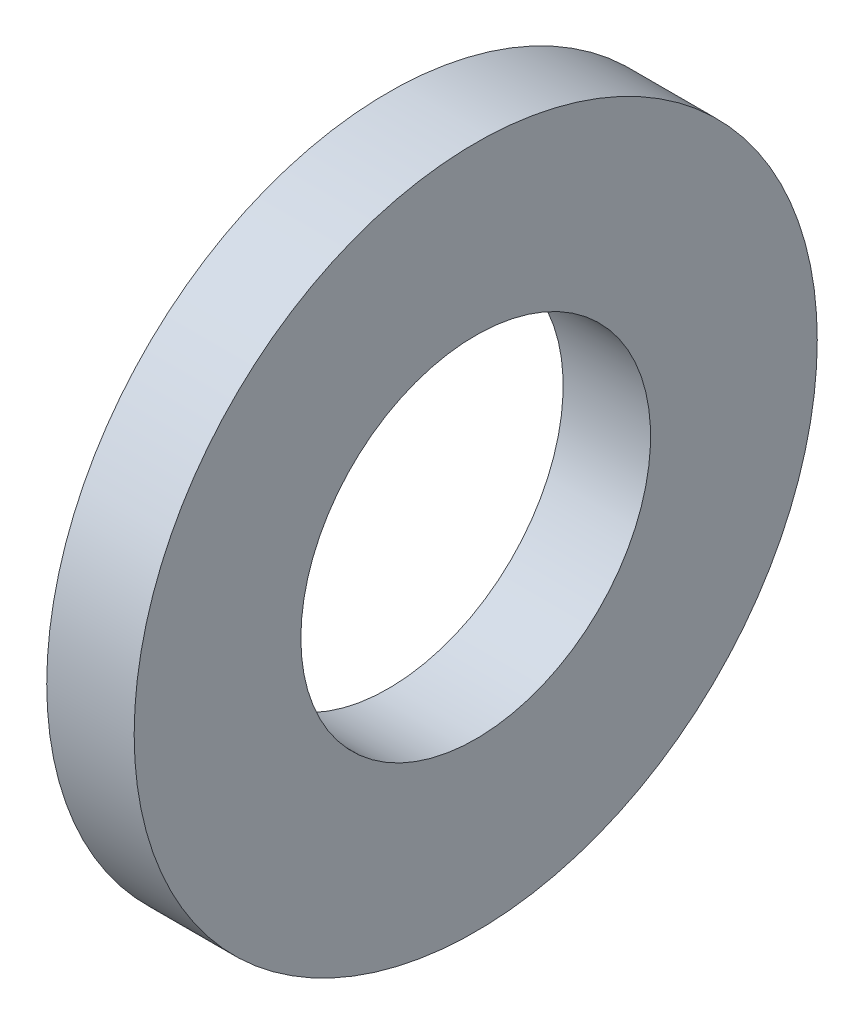
SolidWorks part; units mm, degrees
ref_plane "Plane1" through (0, 0, 0) normal (0, 0, 1) x (1, 0, 0)
ref_plane "Plane2" through (0, 0, 0) normal (0, 1, 0) x (1, 0, 0)
ref_plane "Plane3" through (0, 0, 0) normal (1, 0, 0) x (0, 0, -1)
sketch "Sketch1" plane through (0, 0, 0) normal (0, 0, 1) x (1, 0, 0)
  line L0 (-34.925, 0) -> (9.525, 0) construction
  line L1 (0, 3.2) -> (0, 6.25)
  line L2 (0, 6.25) -> (-1.6, 6.25)
  line L3 (-1.6, 6.25) -> (-1.6, 3.2)
  line L4 (-1.6, 3.2) -> (0, 3.2)
  dimension "Thickness" = 1.6
  dimension "Inside_dia" = 6.4
  dimension "Outside_dia" = 12.5
revolve "Base-Revolve" add sketch "Sketch1" angle 360 about L0
